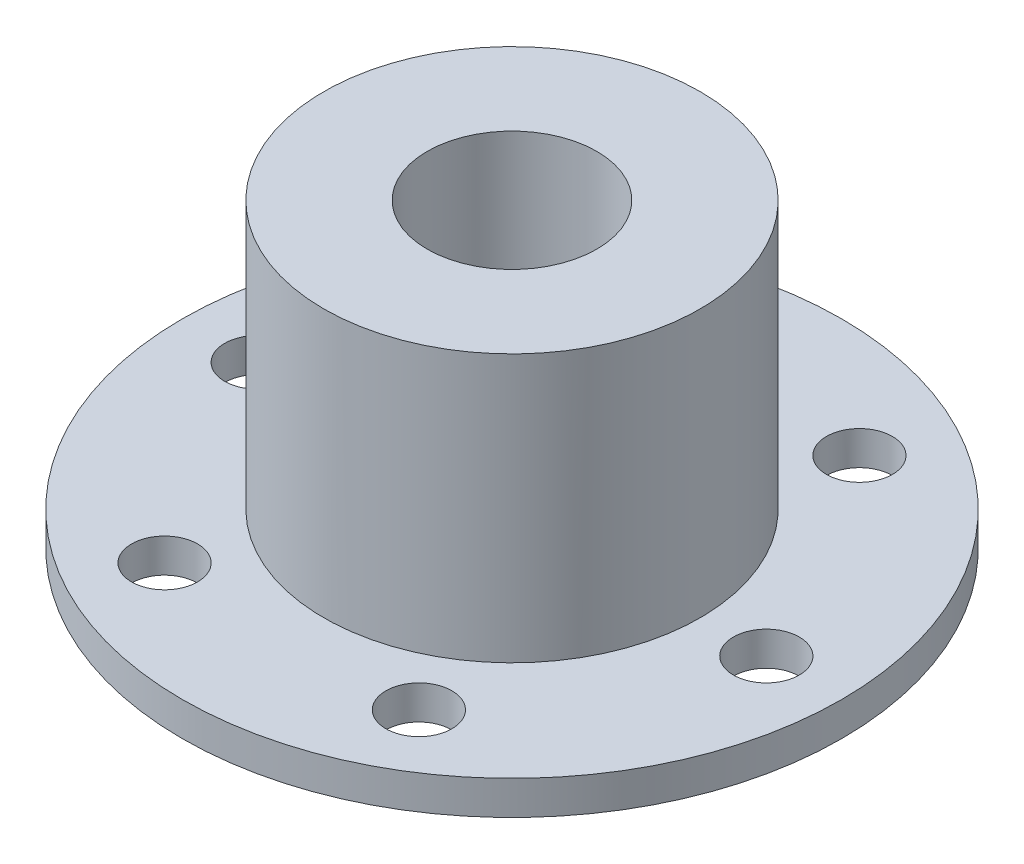
SolidWorks part; units mm, degrees
ref_plane "Front Plane" through (0, 0, 0) normal (0, 0, 1) x (1, 0, 0)
ref_plane "Top Plane" through (0, 0, 0) normal (0, 1, 0) x (1, 0, 0)
ref_plane "Right Plane" through (0, 0, 0) normal (1, 0, 0) x (0, 0, -1)
sketch "Sketch1" plane through (0, 0, 0) normal (0, 1, 0) x (1, 0, 0)
  circle A0 centre (0, 0) radius 9.99
  dimension "D1" = 19.98
extrude "Boss-Extrude1" add sketch "Sketch1" along normal blind 16
sketch "Sketch3" plane through (0, 0, 0) normal (0, -1, 0) x (1, 0, 0)
  circle A0 centre (0, 0) radius 17.5
  point P2 (0, 0)
  dimension "D1" = 35
extrude "Boss-Extrude2" add sketch "Sketch3" against normal blind 1.8
sketch "Sketch4" plane through (0, 0, 0) normal (0, -1, 0) x (1, 0, 0)
  circle A0 centre (0, 0) radius 4.5
  dimension "D1" = 9
extrude "Cut-Extrude1" cut sketch "Sketch4" against normal up to surface (16 mm away) up to face at (0, 16, 9.99)
sketch "Sketch5" plane through (0, 0, 0) normal (0, -1, 0) x (1, 0, 0)
  circle A0 centre (0, 0) radius 4.5 construction
  circle A1 centre (0, 0) radius 17.5
  circle A2 centre (0, 0) radius 17.5
  circle A3 centre (0, 0) radius 4.5
  dimension "D1" = 0
sketch "Sketch6" plane through (0, 0, 0) normal (0, -1, 0) x (1, 0, 0)
  line L0 (4.5, 0) -> (17.5, 0) construction
  circle A0 centre (0, 0) radius 4.5 construction
  circle A1 centre (0, 0) radius 17.5 construction
  circle A2 centre (13.5, 0) radius 1.75
  dimension "D1" = 3.5
  dimension "D2" = 9
extrude "Cut-Extrude2" cut sketch "Sketch6" against normal up to surface (1.8 mm away) up to face at (0, 1.8, -9.99)
pattern_circular "CirPattern1" count 6 every 60 about axis through (0, 0, 0) along (0, 1, 0) of "Cut-Extrude2"
